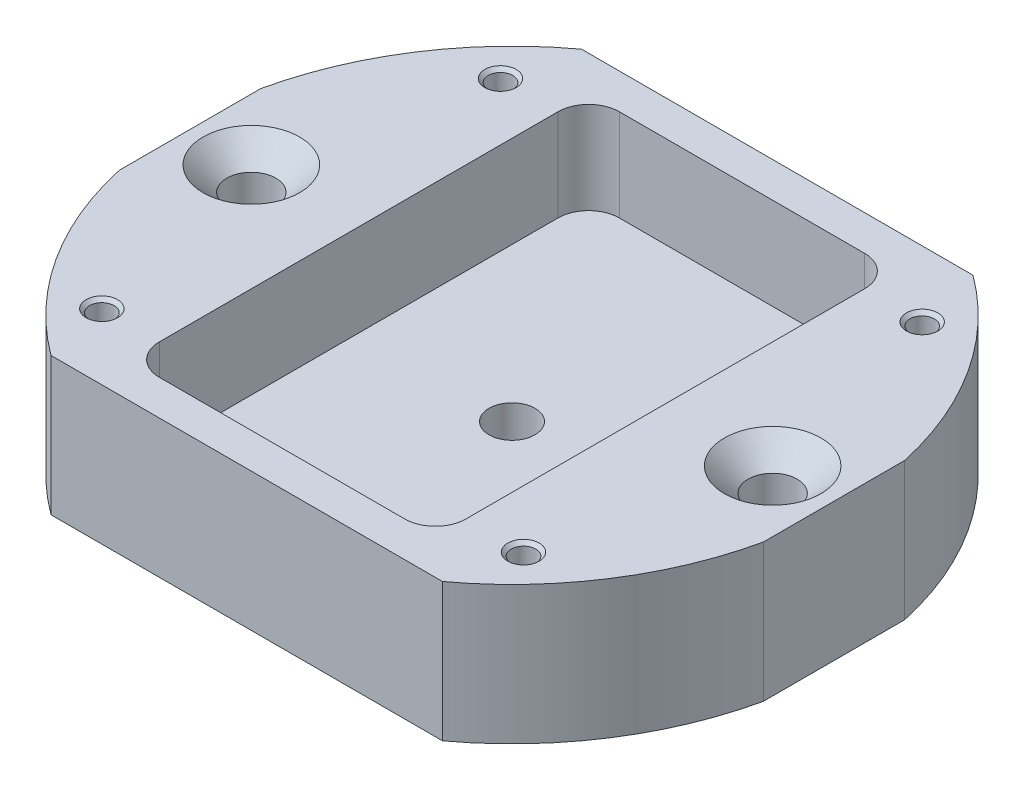
SolidWorks part; units mm, degrees
ref_plane "Front Plane" through (0, 0, 0) normal (0, 0, 1) x (1, 0, 0)
ref_plane "Top Plane" through (0, 0, 0) normal (0, 1, 0) x (1, 0, 0)
ref_plane "Right Plane" through (0, 0, 0) normal (1, 0, 0) x (0, 0, -1)
sketch "Skizze1" plane through (0, 0, 0) normal (0, 1, 0) x (1, 0, 0)
  line L1 (-21, 17.3) -> (21, 17.3)
  line L2 (-21, 17.3) -> (-21, -17.3)
  line L3 (-21, -17.3) -> (21, -17.3)
  line L4 (21, 17.3) -> (21, -17.3)
  line L5 (0, -17.3) -> (0, 17.3) construction
  line L6 (-21, 0) -> (21, 0) construction
  point P204 (0, 0)
  dimension "D1" = 42
  dimension "D2" = 34.6
extrude "Aufsatz-Linear austragen1" add sketch "Skizze1" along normal blind 9
hole_wizard "Formsenkung für M3 Senkschraube mit Schlitz/Kreuzschlitz1" positions "Skizze4" profile "Skizze6" countersink size "M3" standard "DIN"
sketch "Skizze4" plane through (0, 9, 0) normal (0, 1, 0) x (1, 0, 0)
  line L0 (-21, 0) -> (21, 0) construction
  line L1 (-21, 17.3) -> (-21, -17.3) construction
  line L2 (21, -17.3) -> (21, 17.3) construction
  line L4 (0, 16.9356) -> (0, -14.0085) construction
  point P0 (-17, 0)
  point P2 (17, 0)
  dimension "D1" = 34
sketch "Skizze6" plane through (-17, 9, 0) normal (1, 0, 0) x (0, 0, 1)
  line L0 (0, 0) -> (0, 13.3614)
  line L1 (0, 13.3614) -> (1.6, 12.4)
  line L2 (1.6, 12.4) -> (1.6, 1.55)
  line L3 (1.6, 1.55) -> (3.15, 0)
  line L5 (3.15, 0) -> (0, 0)
  line L6 (-1.6, 1.55) -> (-3.15, 0) construction
  line L10 (0, 13.3614) -> (-1.6, 12.4) construction
  line L11 (0, -6.35) -> (0, 107.95) construction
  dimension "Bohrerdurchmesser" = 3.2
  dimension "Bohrungstiefe" = 12.4
  dimension "Senkdurchmesser (Oben)" = 6.3
  dimension "Senkwinkel (Oben)" = 90
  dimension "Spitzenwinkel" = 118
sketch "Skizze17" plane through (0, 9, 0) normal (0, 1, 0) x (1, 0, 0)
  line L1 (-10, 15) -> (10, 15)
  line L2 (-10, 15) -> (-10, -15)
  line L3 (-10, -15) -> (10, -15)
  line L4 (10, 15) -> (10, -15)
  line L5 (0, -15) -> (0, 15) construction
  line L6 (-10, 0) -> (10, 0) construction
  point P300 (0, 0)
  dimension "D1" = 20
  dimension "D2" = 30
extrude "Schnitt-Linear austragen2" cut sketch "Skizze17" against normal blind 6
hole_wizard "M2 Gewindebohrung3" positions "Skizze18" profile "Skizze19" tap size "M2" standard "DIN"
sketch "Skizze18" plane through (0, 9, 0) normal (0, 1, 0) x (1, 0, 0)
  line L0 (0, 17.3) -> (0, -17.3) construction
  line L1 (21, 17.3) -> (-21, 17.3) construction
  line L2 (-21, -17.3) -> (21, -17.3) construction
  line L5 (-21, 0) -> (21, 0) construction
  line L6 (-21, 17.3) -> (-21, -17.3) construction
  line L7 (21, -17.3) -> (21, 17.3) construction
  point P0 (-13.75, 13)
  point P2 (13.75, 13)
  point P4 (13.75, -13)
  point P6 (-13.75, -13)
  dimension "D1" = 27.5
  dimension "D2" = 26
sketch "Skizze19" plane through (-13.75, 9, -13) normal (1, 0, 0) x (0, 0, 1)
  line L0 (0, 0) -> (0, 6.4807)
  line L1 (0, 6.4807) -> (0.8, 6)
  line L2 (0.8, 6) -> (0.8, 0.225)
  line L3 (0.8, 0.225) -> (1.025, 0)
  line L5 (1.025, 0) -> (0, 0)
  line L6 (-0.8, 0.225) -> (-1.025, 0) construction
  line L10 (0, 6.4807) -> (-0.8, 6) construction
  line L11 (0, -6.35) -> (0, 107.95) construction
  dimension "Bohrerdurchmesser" = 1.6
  dimension "Bohrungstiefe" = 6
  dimension "Senkdurchmesser (Oben)" = 2.05
  dimension "Senkwinkel (Oben)" = 90
  dimension "Spitzenwinkel" = 118
cosmetic thread "Bohrungsgewinde9" parameters "D1"=4, "D2"=2
cosmetic thread "Bohrungsgewinde10" parameters "D1"=4, "D2"=2
cosmetic thread "Bohrungsgewinde11" parameters "D1"=4, "D2"=2
cosmetic thread "Bohrungsgewinde12" parameters "D1"=4, "D2"=2
fillet "Verrundung2" radius 2 4 edges at (-10, 6, 15) (10, 6, -15) (10, 6, 15) (-10, 6, -15)
hole_wizard "Ø3.0 (3) Durchmesser Bohrung3" positions "Skizze20" profile "Skizze22" hole size "Ø3.0" standard "DIN" end condition through all
sketch "Skizze20" plane through (0, 3, 0) normal (0, 1, 0) x (1, 0, 0)
  point P0 (0, 0)
sketch "Skizze22" plane through (0, 3, 0) normal (1, 0, 0) x (0, 0, 1)
  line L0 (0, 0) -> (0, 3)
  line L1 (0, 3) -> (1.5, 3)
  line L2 (1.5, 3) -> (1.5, 0)
  line L5 (1.5, 0) -> (0, 0)
  line L11 (0, -6.35) -> (0, 107.95) construction
  dimension "Bohrerdurchmesser" = 3
  dimension "Bohrungstiefe" = 3
sketch "Skizze24" plane through (0, 0, 0) normal (0, -1, 0) x (1, 0, 0)
  circle A0 centre (0, 0) radius 21.5
  dimension "D1" = 43
extrude "Schnitt-Linear-Austragen-Dünn1" cut sketch "Skizze24" against normal blind 10 and the other way blind 10 thin
hole_wizard "Ø2.5 (2.5) Durchmesser Bohrung1" positions "Skizze7" profile "Skizze8" hole size "Ø2.5" standard "DIN"
sketch "Skizze7" plane through (0, 0, 0) normal (0, -1, 0) x (-1, 0, 0)
  line L0 (0, -17.3) -> (0, 17.3) construction
  line L1 (12.7656, -17.3) -> (-12.7656, -17.3) construction
  line L2 (-12.7656, 17.3) -> (12.7656, 17.3) construction
  line L5 (21, 0) -> (-21, 0) construction
  line L6 (21, 4.6098) -> (21, -4.6098) construction
  line L7 (-21, -4.6098) -> (-21, 4.6098) construction
  point P0 (11, 0)
  point P2 (-11, 0)
  dimension "D1" = 22
sketch "Skizze8" plane through (-11, 0, 0) normal (1, 0, 0) x (0, 0, -1)
  line L0 (0, 0) -> (0, 4.7511)
  line L1 (0, 4.7511) -> (1.25, 4)
  line L2 (1.25, 4) -> (1.25, 0)
  line L5 (1.25, 0) -> (0, 0)
  line L10 (0, 4.7511) -> (-1.25, 4) construction
  line L11 (0, -6.35) -> (0, 107.95) construction
  dimension "Bohrerdurchmesser" = 2.5
  dimension "Bohrungstiefe" = 4
  dimension "Spitzenwinkel" = 118
